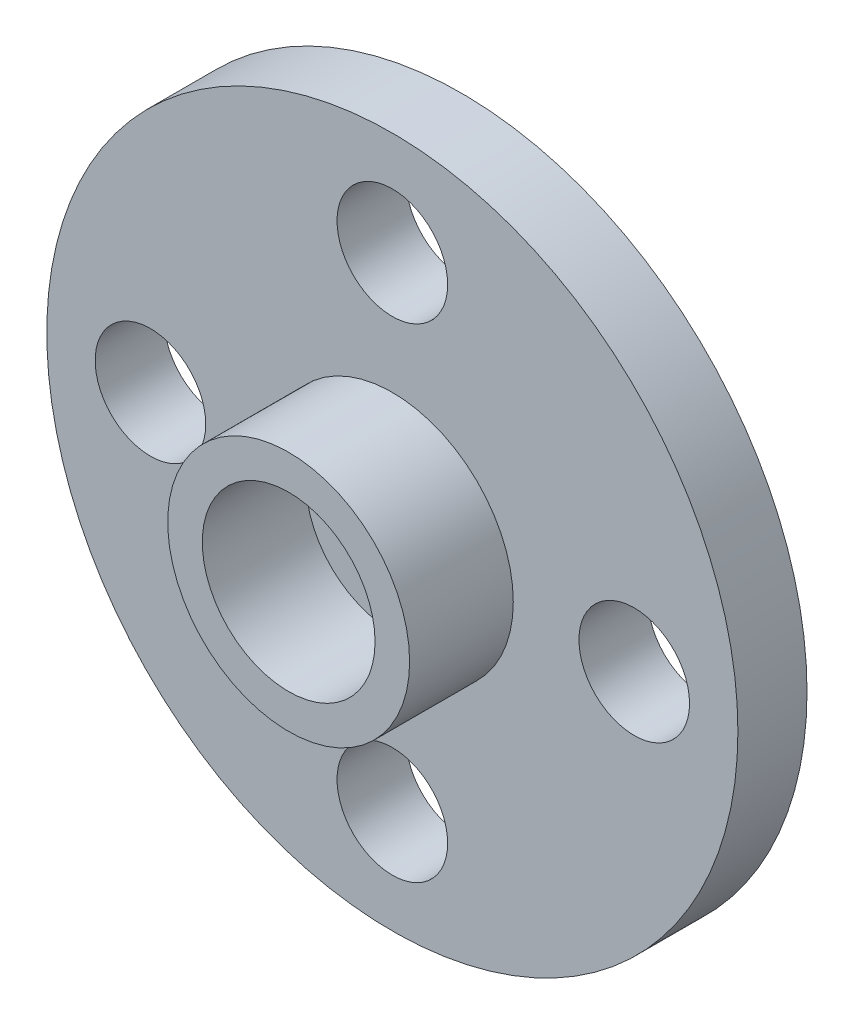
SolidWorks part; units mm, degrees
ref_plane "正面" through (0, 0, 0) normal (0, 0, 1) x (1, 0, 0)
ref_plane "平面" through (0, 0, 0) normal (0, 1, 0) x (1, 0, 0)
ref_plane "右側面" through (0, 0, 0) normal (1, 0, 0) x (0, 0, -1)
sketch "ｽｹｯﾁ1" plane through (0, 0, 0) normal (0, 0, 1) x (1, 0, 0)
  circle A0 centre (0, 0) radius 10
  circle A3 centre (0, 0) radius 7 construction
  circle A4 centre (0, 7) radius 1.6
  circle A5 centre (7, 0) radius 1.6
  circle A6 centre (-7, 0) radius 1.6
  circle A7 centre (0, -7) radius 1.6
  dimension "D1" = 20
  dimension "D2" = 14
  dimension "D3" = 3.2
  dimension "D4" = 3.2
  dimension "D5" = 3.2
  dimension "D6" = 3.2
extrude "ﾎﾞｽ - 押し出し1" add sketch "ｽｹｯﾁ1" along normal blind 2
sketch "ｽｹｯﾁ2" plane through (0, 0, 2) normal (0, 0, 1) x (1, 0, 0)
  circle A0 centre (0, 0) radius 2.5
  circle A1 centre (0, 0) radius 3.5
  dimension "D1" = 5
  dimension "D2" = 1
extrude "ﾎﾞｽ - 押し出し2" add sketch "ｽｹｯﾁ2" along normal blind 3
